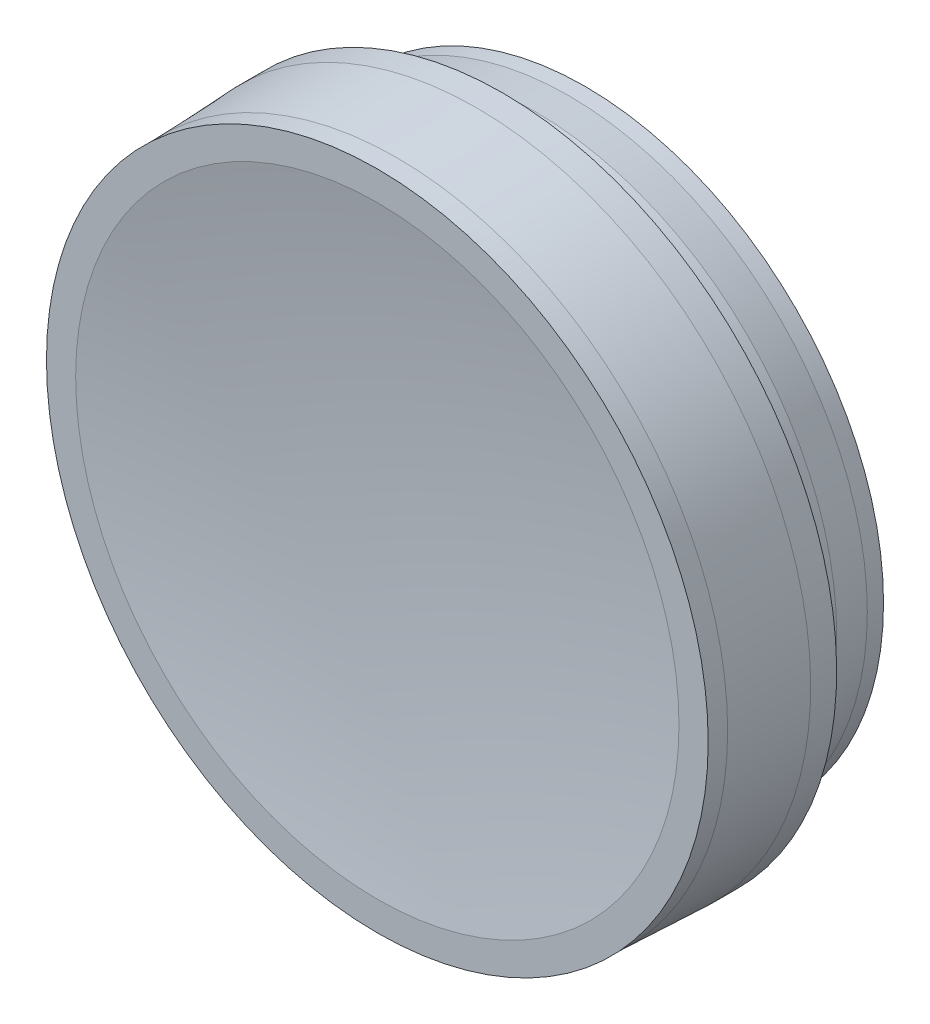
SolidWorks part; units mm, degrees
other "DetailItem1" parameters "D4"=28.9173, "D9"=0.127, "D8"=0.127, "D1"=1.25, "D2"=10.3, "D3"=3, "D5"=1.9303, "D6"=0.5, "D7"=0.5, "D10"=2.4913, "D11"=0.4591, "D12"=0.9368, "D13"=0.5, "D14"=0.2027, "D15"=8.5895
ref_plane "Front Plane" through (0, 0, 0) normal (0, 0, 1) x (1, 0, 0)
ref_plane "Top Plane" through (0, 0, 0) normal (0, 1, 0) x (1, 0, 0)
ref_plane "Right Plane" through (0, 0, 0) normal (1, 0, 0) x (0, 0, -1)
curve "Curve1"
  spline degree 3 poles (0, 0, 0) (0, 0.0167, 0) (0, 0.05, 0) (0, 0.1, 0.0001) (0, 0.15, 0.0002) (0, 0.2, 0.0003) (0, 0.25, 0.0005) (0, 0.3, 0.0008) (0, 0.35, 0.001) (0, 0.4, 0.0014) (0, 0.45, 0.0017) (0, 0.5, 0.0021) (0, 0.55, 0.0026) (0, 0.6, 0.0031) (0, 0.65, 0.0036) (0, 0.7, 0.0042) (0, 0.75, 0.0048) (0, 0.8, 0.0055) (0, 0.85, 0.0062) (0, 0.9, 0.0069) (0, 0.95, 0.0077) (0, 1, 0.0086) (0, 1.05, 0.0094) (0, 1.1, 0.0104) (0, 1.15, 0.0113) (0, 1.2, 0.0123) (0, 1.25, 0.0134) (0, 1.3, 0.0145) (0, 1.35, 0.0156) (0, 1.4, 0.0168) (0, 1.45, 0.018) (0, 1.5, 0.0192) (0, 1.55, 0.0205) (0, 1.6, 0.0219) (0, 1.65, 0.0233) (0, 1.7, 0.0247) (0, 1.75, 0.0262) (0, 1.8, 0.0277) (0, 1.85, 0.0292) (0, 1.9, 0.0308) (0, 1.95, 0.0324) (0, 2, 0.0341) (0, 2.05, 0.0358) (0, 2.1, 0.0376) (0, 2.15, 0.0394) (0, 2.2, 0.0412) (0, 2.25, 0.0431) (0, 2.3, 0.045) (0, 2.35, 0.047) (0, 2.4, 0.049) (0, 2.45, 0.051) (0, 2.5, 0.0531) (0, 2.55, 0.0552) (0, 2.6, 0.0574) (0, 2.65, 0.0595) (0, 2.7, 0.0618) (0, 2.75, 0.064) (0, 2.8, 0.0663) (0, 2.85, 0.0687) (0, 2.9, 0.0711) (0, 2.95, 0.0735) (0, 3, 0.0759) (0, 3.05, 0.0784) (0, 3.1, 0.081) (0, 3.15, 0.0835) (0, 3.2, 0.0861) (0, 3.25, 0.0887) (0, 3.3, 0.0914) (0, 3.35, 0.0941) (0, 3.4, 0.0968) (0, 3.45, 0.0996) (0, 3.5, 0.1024) (0, 3.55, 0.1052) (0, 3.6, 0.1081) (0, 3.65, 0.111) (0, 3.7, 0.1139) (0, 3.75, 0.1169) (0, 3.8, 0.1199) (0, 3.85, 0.1229) (0, 3.9, 0.1259) (0, 3.95, 0.129) (0, 4, 0.1321) (0, 4.05, 0.1352) (0, 4.1, 0.1384) (0, 4.15, 0.1416) (0, 4.2, 0.1448) (0, 4.25, 0.1481) (0, 4.3, 0.1514) (0, 4.35, 0.1547) (0, 4.4, 0.158) (0, 4.45, 0.1614) (0, 4.5, 0.1647) (0, 4.55, 0.1682) (0, 4.6, 0.1716) (0, 4.6333, 0.1739) (0, 4.65, 0.1751) knots 0 0 0 0 0.010743 0.021486 0.032228 0.042971 0.053714 0.064457 0.0752 0.085943 0.096686 0.107429 0.118173 0.128916 0.139659 0.150403 0.161147 0.17189 0.182634 0.193378 0.204122 0.214867 0.225611 0.236356 0.247101 0.257846 0.268591 0.279336 0.290082 0.300827 0.311574 0.32232 0.333066 0.343813 0.35456 0.365307 0.376054 0.386802 0.39755 0.408298 0.419047 0.429796 0.440545 0.451294 0.462044 0.472794 0.483544 0.494295 0.505046 0.515798 0.526549 0.537301 0.548054 0.558807 0.56956 0.580313 0.591067 0.601821 0.612576 0.623331 0.634086 0.644842 0.655598 0.666355 0.677112 0.687869 0.698627 0.709385 0.720143 0.730902 0.741661 0.752421 0.763181 0.773941 0.784702 0.795463 0.806225 0.816987 0.827749 0.838512 0.849275 0.860039 0.870802 0.881567 0.892331 0.903097 0.913862 0.924628 0.935394 0.946161 0.956928 0.967695 0.978463 0.989231 1 1 1 1
sketch "Sketch1" plane through (0, 0, 0) normal (1, 0, 0) x (0, 0, -1)
  line L0 (-1.446, 4.65) -> (-1.446, 5.15)
  line L1 (0, 0) -> (-3, 0)
  line L2 (-3.3763, 5.1) -> (-3.0763, 5.1)
  line L4 (-1.846, 5.15) -> (-3.0763, 5.1)
  line L5 (-0.946, 4.65) -> (-0.4215, 4.5981)
  line L6 (-0.946, 4.65) -> (-1.446, 4.65)
  line L7 (-1.446, 5.15) -> (-1.846, 5.15)
  line L8 (-3.3763, 4.65) -> (-3.3763, 5.1)
  line L9 (5.1891, 0) -> (-7.2359, 0) construction
  line L10 (-0.1715, 4.5981) -> (-0.4215, 4.5981)
  line L11 (-0.158, 4.4) -> (-3.3367, 4.4) construction
  arc A0 (-3, 0) -> (-3.3763, 4.65) centre (-31.9173, 0) ccw
  spline S0 degree 3 poles (3999.5218, -31.3513) (-5.7606, -23.1161) (0.0185, -11.514) (-0.0001, 0.1) (-0.0002, 0.15) (-0.0003, 0.2) (-0.0005, 0.25) (-0.0008, 0.3) (-0.001, 0.35) (-0.0014, 0.4) (-0.0017, 0.45) (-0.0021, 0.5) (-0.0026, 0.55) (-0.0031, 0.6) (-0.0036, 0.65) (-0.0042, 0.7) (-0.0048, 0.75) (-0.0055, 0.8) (-0.0062, 0.85) (-0.0069, 0.9) (-0.0077, 0.95) (-0.0086, 1) (-0.0094, 1.05) (-0.0104, 1.1) (-0.0113, 1.15) (-0.0123, 1.2) (-0.0134, 1.25) (-0.0145, 1.3) (-0.0156, 1.35) (-0.0168, 1.4) (-0.018, 1.45) (-0.0192, 1.5) (-0.0205, 1.55) (-0.0219, 1.6) (-0.0233, 1.65) (-0.0247, 1.7) (-0.0262, 1.75) (-0.0277, 1.8) (-0.0292, 1.85) (-0.0308, 1.9) (-0.0324, 1.95) (-0.0341, 2) (-0.0358, 2.05) (-0.0376, 2.1) (-0.0394, 2.15) (-0.0412, 2.2) (-0.0431, 2.25) (-0.045, 2.3) (-0.047, 2.35) (-0.049, 2.4) (-0.051, 2.45) (-0.0531, 2.5) (-0.0552, 2.55) (-0.0574, 2.6) (-0.0595, 2.65) (-0.0618, 2.7) (-0.064, 2.75) (-0.0663, 2.8) (-0.0687, 2.85) (-0.0711, 2.9) (-0.0735, 2.95) (-0.0759, 3) (-0.0784, 3.05) (-0.081, 3.1) (-0.0835, 3.15) (-0.0861, 3.2) (-0.0887, 3.25) (-0.0914, 3.3) (-0.0941, 3.35) (-0.0968, 3.4) (-0.0996, 3.45) (-0.1024, 3.5) (-0.1052, 3.55) (-0.1081, 3.6) (-0.111, 3.65) (-0.1139, 3.7) (-0.1169, 3.75) (-0.1199, 3.8) (-0.1229, 3.85) (-0.1259, 3.9) (-0.129, 3.95) (-0.1321, 4) (-0.1352, 4.05) (-0.1384, 4.1) (-0.1416, 4.15) (-0.1448, 4.2) (-0.1481, 4.25) (-0.1514, 4.3) (-0.1547, 4.35) (-0.158, 4.4) (-0.1614, 4.45) (-0.1647, 4.5) (-0.1682, 4.55) (-1.1656, 19.0508) (-6.785, 33.2147) (3986.6733, 324.3733) knots -7.453775 -7.453775 -7.453775 -7.453775 0.010743 0.021486 0.032228 0.042971 0.053714 0.064457 0.0752 0.085943 0.096686 0.107429 0.118173 0.128916 0.139659 0.150403 0.161147 0.17189 0.182634 0.193378 0.204122 0.214867 0.225611 0.236356 0.247101 0.257846 0.268591 0.279336 0.290082 0.300827 0.311574 0.32232 0.333066 0.343813 0.35456 0.365307 0.376054 0.386802 0.39755 0.408298 0.419047 0.429796 0.440545 0.451294 0.462044 0.472794 0.483544 0.494295 0.505046 0.515798 0.526549 0.537301 0.548054 0.558807 0.56956 0.580313 0.591067 0.601821 0.612576 0.623331 0.634086 0.644842 0.655598 0.666355 0.677112 0.687869 0.698627 0.709385 0.720143 0.730902 0.741661 0.752421 0.763181 0.773941 0.784702 0.795463 0.806225 0.816987 0.827749 0.838512 0.849275 0.860039 0.870802 0.881567 0.892331 0.903097 0.913862 0.924628 0.935394 0.946161 0.956928 0.967695 0.978463 0.989231 10.336559 10.336559 10.336559 10.336559 only from (0, 0) to (-0.1751, 4.65) construction
  spline S1 degree 3 poles (0, 0) (0, 0.0167) (0, 0.05) (-0.0001, 0.1) (-0.0002, 0.15) (-0.0003, 0.2) (-0.0005, 0.25) (-0.0008, 0.3) (-0.001, 0.35) (-0.0014, 0.4) (-0.0017, 0.45) (-0.0021, 0.5) (-0.0026, 0.55) (-0.0031, 0.6) (-0.0036, 0.65) (-0.0042, 0.7) (-0.0048, 0.75) (-0.0055, 0.8) (-0.0062, 0.85) (-0.0069, 0.9) (-0.0077, 0.95) (-0.0086, 1) (-0.0094, 1.05) (-0.0104, 1.1) (-0.0113, 1.15) (-0.0123, 1.2) (-0.0134, 1.25) (-0.0145, 1.3) (-0.0156, 1.35) (-0.0168, 1.4) (-0.018, 1.45) (-0.0192, 1.5) (-0.0205, 1.55) (-0.0219, 1.6) (-0.0233, 1.65) (-0.0247, 1.7) (-0.0262, 1.75) (-0.0277, 1.8) (-0.0292, 1.85) (-0.0308, 1.9) (-0.0324, 1.95) (-0.0341, 2) (-0.0358, 2.05) (-0.0376, 2.1) (-0.0394, 2.15) (-0.0412, 2.2) (-0.0431, 2.25) (-0.045, 2.3) (-0.047, 2.35) (-0.049, 2.4) (-0.051, 2.45) (-0.0531, 2.5) (-0.0552, 2.55) (-0.0574, 2.6) (-0.0595, 2.65) (-0.0618, 2.7) (-0.064, 2.75) (-0.0663, 2.8) (-0.0687, 2.85) (-0.0711, 2.9) (-0.0735, 2.95) (-0.0759, 3) (-0.0784, 3.05) (-0.081, 3.1) (-0.0835, 3.15) (-0.0861, 3.2) (-0.0887, 3.25) (-0.0914, 3.3) (-0.0941, 3.35) (-0.0968, 3.4) (-0.0996, 3.45) (-0.1024, 3.5) (-0.1052, 3.55) (-0.1081, 3.6) (-0.111, 3.65) (-0.1139, 3.7) (-0.1169, 3.75) (-0.1199, 3.8) (-0.1229, 3.85) (-0.1259, 3.9) (-0.129, 3.95) (-0.1321, 4) (-0.1352, 4.05) (-0.1384, 4.1) (-0.1416, 4.15) (-0.1448, 4.2) (-0.1481, 4.25) (-0.1514, 4.3) (-0.1547, 4.35) (-0.158, 4.4) (-0.1614, 4.45) (-0.1647, 4.5) (-0.1681, 4.5494) (-0.1704, 4.5821) (-0.1715, 4.5981) knots 0 0 0 0 0.010743 0.021486 0.032228 0.042971 0.053714 0.064457 0.0752 0.085943 0.096686 0.107429 0.118173 0.128916 0.139659 0.150403 0.161147 0.17189 0.182634 0.193378 0.204122 0.214867 0.225611 0.236356 0.247101 0.257846 0.268591 0.279336 0.290082 0.300827 0.311574 0.32232 0.333066 0.343813 0.35456 0.365307 0.376054 0.386802 0.39755 0.408298 0.419047 0.429796 0.440545 0.451294 0.462044 0.472794 0.483544 0.494295 0.505046 0.515798 0.526549 0.537301 0.548054 0.558807 0.56956 0.580313 0.591067 0.601821 0.612576 0.623331 0.634086 0.644842 0.655598 0.666355 0.677112 0.687869 0.698627 0.709385 0.720143 0.730902 0.741661 0.752421 0.763181 0.773941 0.784702 0.795463 0.806225 0.816987 0.827749 0.838512 0.849275 0.860039 0.870802 0.881567 0.892331 0.903097 0.913862 0.924628 0.935394 0.946161 0.956928 0.967695 0.978463 0.988822 0.988822 0.988822 0.988822
revolve "Revolve1" add sketch "Sketch1" angle 360 about L9
sketch "Sketch2" plane through (0, 0, 1.446) normal (0, 0, -1) x (-1, 0, 0)
  line L0 (4.225, -1.9421) -> (8.15, -1.25)
  line L1 (4.225, 1.9421) -> (8.15, 1.25)
  line L2 (4.225, 1.9421) -> (4.225, -1.9421)
  line L3 (4.225, 0) -> (8.15, 0) construction
  line L4 (8.15, 1.25) -> (8.15, -1.25)
  circle A0 centre (0, 0) radius 5.15 construction
  circle A2 centre (0, 0) radius 4.65 construction
  dimension "D1" = 2.5
  dimension "D2" = 20
  dimension "D3" = 3
extrude "Gate" [suppressed] add sketch "Sketch2" against normal blind 1.5 draft 3
fillet "Fillet1" [suppressed] radius 0.7874
